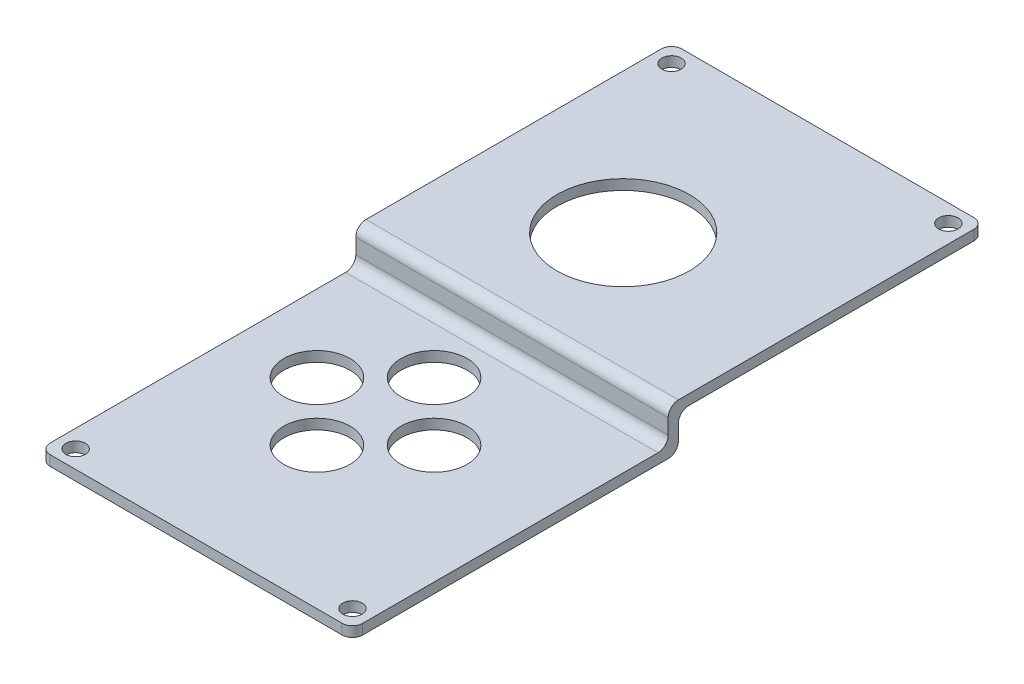
SolidWorks part; units mm, degrees
ref_plane "Front Plane" through (0, 0, 0) normal (0, 0, 1) x (1, 0, 0)
ref_plane "Top Plane" through (0, 0, 0) normal (0, 1, 0) x (1, 0, 0)
ref_plane "Right Plane" through (0, 0, 0) normal (1, 0, 0) x (0, 0, -1)
sketch "Sketch2" plane through (0, 0, 0) normal (1, 0, 0) x (0, 0, -1)
  line L0 (0, 0) -> (60, 0)
  line L1 (0, 0) -> (0, -7)
  line L2 (0, -7) -> (-64, -7)
  line L3 (60, 0) -> (60, 2)
  line L4 (60, 2) -> (-2, 2)
  line L5 (-2, 2) -> (-2, -5)
  line L6 (-2, -5) -> (-64, -5)
  line L7 (-64, -5) -> (-64, -7)
  dimension "D1" = 60
  dimension "D2" = 7
  dimension "D3" = 64
  dimension "D4" = 2
  dimension "D5" = 2
  dimension "D6" = 2
extrude "Boss-Extrude1" add sketch "Sketch2" along normal blind 61.34
sketch "Sketch3" plane through (0, 2, 0) normal (0, 1, 0) x (1, 0, 0)
  line L0 (27.5, 60) -> (27.5, 23) construction
  line L1 (61.34, 60) -> (0, 60) construction
  line L2 (0, 60) -> (0, -2) construction
  line L3 (0, 56.5) -> (3.5, 56.5) construction
  line L4 (61.34, 56.5) -> (57.84, 56.5) construction
  line L6 (61.34, 60) -> (61.34, -2) construction
  circle A0 centre (27.5, 23) radius 13
  circle A1 centre (57.84, 56.5) radius 1.9
  circle A2 centre (3.5, 56.5) radius 1.9
  dimension "D3" = 26
  dimension "D8" = 3.8
  dimension "D9" = 3.8
  dimension "D1" = 37
  dimension "D2" = 27.5
  dimension "D4" = 3.5
  dimension "D5" = 3.5
  dimension "D6" = 3.5
  dimension "D7" = 3.5
sketch "Sketch4" plane through (0, -5, 0) normal (0, 1, 0) x (1, 0, 0)
  line L0 (15.07, -64) -> (15.07, -24.7) construction
  line L1 (61.34, -64) -> (0, -64) construction
  line L2 (15.07, -24.7) -> (0, -24.7) construction
  line L3 (0, -2) -> (0, -64) construction
  line L4 (15.07, -24.7) -> (38.07, -24.7) construction
  line L5 (26.57, -24.7) -> (26.57, -36.2) construction
  line L6 (61.34, -60.5) -> (57.84, -60.5) construction
  line L7 (61.34, -2) -> (61.34, -64) construction
  line L8 (0, -60.5) -> (3.5, -60.5) construction
  line L9 (26.57, -24.7) -> (26.57, -13.2) construction
  circle A0 centre (38.07, -24.7) radius 6.5
  circle A1 centre (26.57, -36.2) radius 6.5
  circle A2 centre (15.07, -24.7) radius 6.5
  circle A3 centre (26.57, -13.2) radius 6.5
  circle A4 centre (57.84, -60.5) radius 1.9
  circle A5 centre (3.5, -60.5) radius 1.9
  dimension "D5" = 13
  dimension "D6" = 13
  dimension "D7" = 13
  dimension "D8" = 13
  dimension "D13" = 3.8
  dimension "D14" = 3.8
  dimension "D1" = 39.3
  dimension "D2" = 15.07
  dimension "D3" = 23
  dimension "D4" = 11.5
  dimension "D9" = 3.5
  dimension "D10" = 3.5
  dimension "D11" = 3.5
  dimension "D12" = 3.5
  dimension "D15" = 11.5
extrude "Cut-Extrude1" cut sketch "Sketch3" against normal through all contours A0
extrude "Cut-Extrude2" cut sketch "Sketch4" against normal through all
fillet "Fillet1" radius 2 4 edges at (30.67, 0, 0) (30.67, -7, 0) (30.67, 2, 2) (30.67, -5, 2)
fillet "Fillet3" radius 2 4 edges at (61.34, 1, -60) (61.34, -6, 64) (0, -6, 64) (0, 1, -60)
